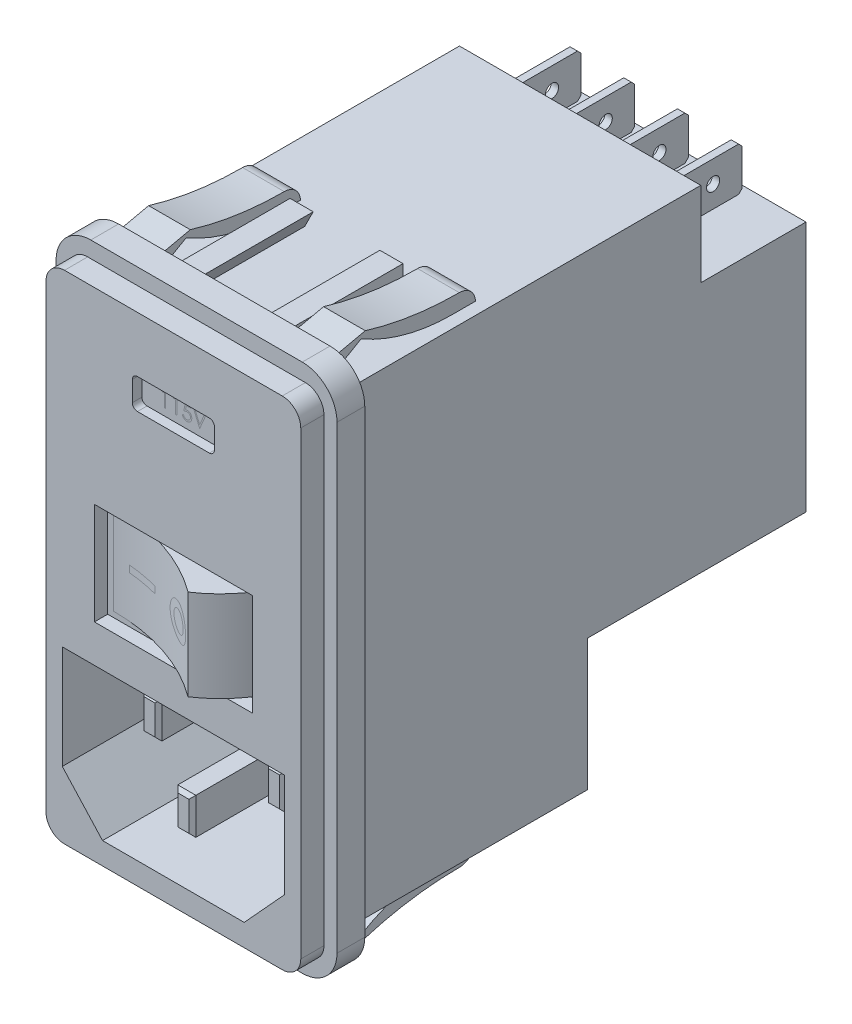
SolidWorks part; units mm, degrees
ref_plane "Front Plane" through (0, 0, 0) normal (0, 0, 1) x (1, 0, 0)
ref_plane "Top Plane" through (0, 0, 0) normal (0, 1, 0) x (1, 0, 0)
ref_plane "Right Plane" through (0, 0, 0) normal (1, 0, 0) x (0, 0, -1)
sketch "Sketch1" plane through (0, 0, 0) normal (0, 0, 1) x (1, 0, 0)
  line L1 (-11.6014, -29.0386) -> (11.6014, -29.0386)
  line L2 (-15.4114, -25.2285) -> (-15.4114, 25.2285)
  line L3 (-11.6014, 29.0386) -> (11.6014, 29.0386)
  line L4 (15.4115, -25.2285) -> (15.4115, 25.2285)
  line L5 (-15.4114, -29.0386) -> (15.4115, 29.0386) construction
  line L6 (-15.4114, 29.0386) -> (15.4115, -29.0386) construction
  arc A0 (-11.6014, -29.0386) -> (-15.4114, -25.2285) centre (-11.6014, -25.2286) cw
  arc A1 (11.6014, -29.0386) -> (15.4115, -25.2285) centre (11.6015, -25.2286) ccw
  arc A2 (11.6014, 29.0386) -> (15.4115, 25.2285) centre (11.6015, 25.2286) cw
  arc A3 (-15.4114, 25.2285) -> (-11.6014, 29.0386) centre (-11.6014, 25.2286) cw
  point P0 (0, 0)
  dimension "D3" = 3.81
  dimension "D1" = 58.0771
  dimension "D2" = 30.8229
extrude "Boss-Extrude1" add sketch "Sketch1" against normal blind 5.588
sketch "Sketch2" plane through (0, 0, 0) normal (0, 0, 1) x (1, 0, 0)
  line L0 (11.6014, 29.0386) -> (-11.6014, 29.0386) construction
  line L1 (-11.9443, -27.2606) -> (11.9443, -27.2606)
  line L2 (-13.9764, -25.2285) -> (-13.9764, 25.2285)
  line L3 (-11.9443, 27.2606) -> (11.9443, 27.2606)
  line L4 (13.9764, -25.2285) -> (13.9764, 25.2285)
  line L5 (-13.9764, -27.2606) -> (13.9764, 27.2606) construction
  line L6 (-13.9764, 27.2606) -> (13.9764, -27.2606) construction
  line L7 (15.4115, -25.2286) -> (15.4115, 25.2285) construction
  line L12 (-11.6014, -29.0386) -> (11.6014, -29.0386)
  line L13 (15.4115, -25.2286) -> (15.4115, 25.2285)
  line L14 (11.6014, 29.0386) -> (-11.6014, 29.0386)
  line L15 (-15.4114, 25.2285) -> (-15.4114, -25.2285)
  line L16 (-11.6014, -29.0386) -> (11.6014, -29.0386)
  line L17 (15.4115, -25.2286) -> (15.4115, 25.2285)
  line L18 (11.6014, 29.0386) -> (-11.6014, 29.0386)
  line L19 (-15.4114, 25.2285) -> (-15.4114, -25.2285)
  arc A0 (-11.9443, -27.2606) -> (-13.9764, -25.2285) centre (-11.9444, -25.2286) cw
  arc A1 (11.9443, -27.2606) -> (13.9764, -25.2285) centre (11.9444, -25.2286) ccw
  arc A2 (11.9443, 27.2606) -> (13.9764, 25.2285) centre (11.9444, 25.2286) cw
  arc A3 (-13.9764, 25.2285) -> (-11.9443, 27.2606) centre (-11.9444, 25.2286) cw
  arc A8 (-15.4114, -25.2285) -> (-11.6014, -29.0386) centre (-11.6014, -25.2286) ccw
  arc A9 (11.6014, -29.0386) -> (15.4115, -25.2286) centre (11.6015, -25.2286) ccw
  arc A10 (15.4115, 25.2285) -> (11.6014, 29.0386) centre (11.6015, 25.2286) ccw
  arc A11 (-11.6014, 29.0386) -> (-15.4114, 25.2285) centre (-11.6014, 25.2286) ccw
  arc A12 (-15.4114, -25.2285) -> (-11.6014, -29.0386) centre (-11.6014, -25.2286) ccw
  arc A13 (11.6014, -29.0386) -> (15.4115, -25.2286) centre (11.6015, -25.2286) ccw
  arc A14 (15.4115, 25.2285) -> (11.6014, 29.0386) centre (11.6015, 25.2286) ccw
  arc A15 (-11.6014, 29.0386) -> (-15.4114, 25.2285) centre (-11.6014, 25.2286) ccw
  point P0 (0, 0)
  dimension "D3" = 2.032
  dimension "D1" = 1.778
  dimension "D2" = 1.4351
  dimension "D4" = 0
extrude "Cut-Extrude1" cut sketch "Sketch2" against normal blind 2.54
sketch "Sketch4" plane through (0, 0, -5.588) normal (0, 0, -1) x (-1, 0, 0)
  line L1 (-13.2398, -25.6096) -> (13.2397, -25.6096)
  line L2 (-13.2398, -25.6096) -> (-13.2398, 25.6096)
  line L3 (-13.2398, 25.6096) -> (13.2397, 25.6096)
  line L4 (13.2397, -25.6096) -> (13.2397, 25.6096)
  line L5 (-13.2398, -25.6096) -> (13.2397, 25.6096) construction
  line L6 (-13.2398, 25.6096) -> (13.2397, -25.6096) construction
  point P0 (0, 0)
  dimension "D1" = 51.2191
  dimension "D2" = 26.4795
extrude "Boss-Extrude2" add sketch "Sketch4" along normal blind 50.5841
sketch "Sketch3" plane through (0, 0, 0) normal (0, 0, 1) x (1, 0, 0)
  line L0 (-12.192, -20.0089) -> (-7.7724, -24.8476)
  line L1 (-12.192, -20.0089) -> (12.192, -20.0089) construction
  line L2 (-12.192, -20.0089) -> (-12.192, -8.6424)
  line L3 (-12.192, -8.6424) -> (12.192, -8.6424)
  line L4 (12.192, -20.0089) -> (12.192, -8.6424)
  line L5 (-12.192, -20.0089) -> (12.192, -8.6424) construction
  line L6 (-12.192, -8.6424) -> (12.192, -20.0089) construction
  line L7 (-7.7724, -24.8476) -> (7.7724, -24.8476)
  line L8 (7.7724, -24.8476) -> (12.192, -20.0089)
  line L9 (-11.6014, -29.0386) -> (11.6014, -29.0386) construction
  point P0 (0, -14.3256)
  point P5 (0, -24.8476)
  dimension "D1" = 24.384
  dimension "D2" = 11.3665
  dimension "D3" = 16.2052
  dimension "D4" = 4.4196
  dimension "D5" = 4.191
extrude "Cut-Extrude2" cut sketch "Sketch3" against normal blind 16.51
sketch "Sketch5" plane through (0, 0, -16.51) normal (0, 0, 1) x (1, 0, 0)
  line L0 (0, -8.6424) -> (0, -24.8476) construction
  line L1 (-7.8232, -12.7191) -> (-5.842, -12.7191)
  line L2 (-7.8232, -12.7191) -> (-7.8232, -16.7196)
  line L3 (-7.8232, -16.7196) -> (-5.842, -16.7196)
  line L4 (-5.842, -12.7191) -> (-5.842, -16.7196)
  line L5 (5.842, -12.7191) -> (7.8232, -12.719)
  line L6 (5.842, -12.7191) -> (5.842, -16.7196)
  line L7 (5.842, -16.7196) -> (7.8232, -16.7195)
  line L8 (7.8232, -12.719) -> (7.8232, -16.7195)
  line L9 (-0.9906, -16.8974) -> (0.9906, -16.8974) construction
  line L10 (-0.9906, -16.8974) -> (-0.9906, -20.8979) construction
  line L11 (-0.9906, -20.8979) -> (0.9906, -20.8979) construction
  line L12 (0.9906, -16.8974) -> (0.9906, -20.8979) construction
  line L13 (12.192, -8.6424) -> (-12.192, -8.6424) construction
  line L14 (-7.7724, -24.8476) -> (7.7724, -24.8476) construction
  line L15 (-7.7724, -24.8476) -> (7.7724, -24.8476) construction
  line L16 (-12.192, -8.6424) -> (-12.192, -20.0089) construction
  dimension "D1" = 1.9812
  dimension "D2" = 4.0005
  dimension "D3" = 8.255
  dimension "D4" = 8.128
  dimension "D5" = 4.3688
extrude "Boss-Extrude3" add sketch "Sketch5" along normal blind 12.3063
sketch "Sketch6" plane through (0, 0, -16.51) normal (0, 0, 1) x (1, 0, 0)
  line L0 (-0.9906, -16.8974) -> (0.9906, -16.8974) construction
  line L1 (0.9906, -16.8974) -> (0.9906, -20.8979) construction
  line L2 (-0.9906, -20.8979) -> (0.9906, -20.8979) construction
  line L3 (-0.9906, -16.8974) -> (-0.9906, -20.8979) construction
  line L4 (-0.9906, -16.8974) -> (0.9906, -16.8974)
  line L5 (0.9906, -16.8974) -> (0.9906, -20.8979)
  line L6 (-0.9906, -20.8979) -> (0.9906, -20.8979)
  line L7 (-0.9906, -16.8974) -> (-0.9906, -20.8979)
extrude "Boss-Extrude4" add sketch "Sketch6" along normal blind 15.4178
sketch "Sketch7" plane through (0, 0, 0) normal (0, 0, 1) x (1, 0, 0)
  line L0 (12.192, -8.6424) -> (-12.192, -8.6424) construction
  line L1 (-8.6678, 6.6611) -> (8.6677, 6.6611)
  line L2 (-8.6678, 6.6611) -> (-8.6677, -4.5149)
  line L3 (-8.6677, -4.5149) -> (8.6677, -4.5149)
  line L4 (8.6677, 6.6611) -> (8.6677, -4.5149)
  line L5 (-8.6678, 6.6611) -> (8.6677, -4.5149) construction
  line L6 (-8.6677, -4.5149) -> (8.6677, 6.6611) construction
  point P0 (0, 1.0731)
  dimension "D1" = 17.3355
  dimension "D2" = 11.176
  dimension "D3" = 4.1275
extrude "Cut-Extrude3" cut sketch "Sketch7" against normal blind 1.4605
ref_plane "Plane1" through (0, 1.0731, 0) normal (0, -1, 0) x (-1, 0, 0)
sketch "Sketch8" plane through (0, 1.0731, 0) normal (0, -1, 0) x (-1, 0, 0)
  line L0 (8.0582, 1.4605) -> (-8.0582, 1.4605)
  line L1 (-8.6677, 1.4605) -> (8.6678, 1.4605) construction
  line L2 (-4.1974, -2.5908) -> (-4.1974, 1.4605) construction
  line L3 (8.0582, 1.4605) -> (8.0582, -2.5908) construction
  line L4 (8.0582, -2.5908) -> (-8.0582, -2.5908) construction
  line L5 (-8.0582, -2.5908) -> (-8.0582, 1.4605) construction
  line L6 (8.6678, 1.4605) -> (8.6678, 0) construction
  arc A0 (-8.0582, 1.4605) -> (-4.1974, -2.5908) centre (2.8401, 7.981) ccw
  arc A1 (-4.1974, -2.5908) -> (8.0582, 1.4605) centre (8.0582, -19.1021) cw
  point P12 (0, -2.5908)
  dimension "D4" = 12.7
  dimension "D1" = 4.0513
  dimension "D2" = 0.6096
  dimension "D3" = 3.8608
extrude "Boss-Extrude5" add sketch "Sketch8" against normal offset from surface 0.6096 and the other way offset from surface (4.9784 mm away) 0.6096 up to face at (0, 6.6611, -0.7302) other way up to face at (0, -4.5149, -0.7302)
sketch "Sketch9" plane through (0, 0, 0) normal (0, 0, 1) x (1, 0, 0)
  line L0 (11.9443, 27.2606) -> (-11.9443, 27.2606) construction
  line L1 (-3.9497, 17.8372) -> (3.9497, 17.8372)
  line L2 (-4.5085, 18.396) -> (-4.5085, 20.6057)
  line L3 (-3.9497, 21.1646) -> (3.9497, 21.1646)
  line L4 (4.5085, 18.396) -> (4.5085, 20.6057)
  line L5 (-4.5085, 17.8372) -> (4.5085, 21.1646) construction
  line L6 (-4.5085, 21.1646) -> (4.5085, 17.8372) construction
  arc A0 (3.9497, 17.8372) -> (4.5085, 18.396) centre (3.9497, 18.3959) ccw
  arc A1 (3.9497, 21.1646) -> (4.5085, 20.6057) centre (3.9497, 20.6058) cw
  arc A2 (-3.9497, 17.8372) -> (-4.5085, 18.396) centre (-3.9497, 18.3959) cw
  arc A3 (-4.5085, 20.6057) -> (-3.9497, 21.1646) centre (-3.9497, 20.6058) cw
  point P0 (0, 19.5008)
  dimension "D4" = 0.5588
  dimension "D1" = 9.017
  dimension "D2" = 3.3274
  dimension "D3" = 6.096
extrude "Cut-Extrude4" cut sketch "Sketch9" against normal blind 1.0541
sketch "Sketch10" plane through (13.2398, 0, 0) normal (1, 0, 0) x (0, 0, -1)
  line L1 (56.1721, 25.6096) -> (44.6278, 25.6096)
  line L2 (56.1721, 25.6096) -> (56.1721, 16.3513)
  line L3 (56.1721, 16.3513) -> (44.6278, 16.3513)
  line L4 (44.6278, 25.6096) -> (44.6278, 16.3513)
  line L5 (56.1721, -25.6096) -> (32.1945, -25.6096)
  line L6 (56.1721, -25.6096) -> (56.1721, -11.2078)
  line L7 (56.1721, -11.2078) -> (32.1945, -11.2078)
  line L8 (32.1945, -25.6096) -> (32.1945, -11.2078)
  dimension "D1" = 23.9776
  dimension "D2" = 14.4018
  dimension "D3" = 9.2583
  dimension "D4" = 11.5443
extrude "Cut-Extrude5" cut sketch "Sketch10" against normal through all
sketch "Sketch11" plane through (0, 0, -44.6278) normal (0, 0, -1) x (-1, 0, 0)
  line L0 (0, 0) -> (0, 25.6096) construction
  line L1 (-9.2456, 23.4633) -> (-8.4328, 23.4633)
  line L2 (-9.2456, 23.4633) -> (-9.2456, 18.6754)
  line L3 (-9.2456, 18.6754) -> (-8.4328, 18.6754)
  line L4 (-8.4328, 23.4633) -> (-8.4328, 18.6754)
  line L5 (-9.2456, 23.4633) -> (-8.4328, 18.6754) construction
  line L6 (-9.2456, 18.6754) -> (-8.4328, 23.4633) construction
  line L7 (-3.3528, 23.4633) -> (-2.54, 23.4633)
  line L8 (-3.3528, 23.4633) -> (-3.3528, 18.6754)
  line L9 (-3.3528, 18.6754) -> (-2.54, 18.6754)
  line L10 (-2.54, 23.4633) -> (-2.54, 18.6754)
  line L11 (-3.3528, 23.4633) -> (-2.54, 18.6754) construction
  line L12 (-3.3528, 18.6754) -> (-2.54, 23.4633) construction
  line L13 (2.54, 23.4633) -> (3.3528, 23.4633)
  line L14 (2.54, 23.4633) -> (2.54, 18.6754)
  line L15 (2.54, 18.6754) -> (3.3528, 18.6754)
  line L16 (3.3528, 23.4633) -> (3.3528, 18.6754)
  line L17 (2.54, 23.4633) -> (3.3528, 18.6754) construction
  line L18 (2.54, 18.6754) -> (3.3528, 23.4633) construction
  line L19 (8.4328, 23.4633) -> (9.2456, 23.4633)
  line L20 (8.4328, 23.4633) -> (8.4328, 18.6754)
  line L21 (8.4328, 18.6754) -> (9.2456, 18.6754)
  line L22 (9.2456, 23.4633) -> (9.2456, 18.6754)
  line L23 (8.4328, 23.4633) -> (9.2456, 18.6754) construction
  line L24 (8.4328, 18.6754) -> (9.2456, 23.4633) construction
  line L25 (13.2397, 25.6096) -> (-13.2398, 25.6096) construction
  point P0 (-8.8392, 21.0693)
  point P5 (-2.9464, 21.0693)
  point P10 (2.9464, 21.0693)
  point P15 (8.8392, 21.0693)
  dimension "D1" = 4.7879
  dimension "D2" = 0.8128
  dimension "D3" = 5.08
  dimension "D4" = 5.08
  dimension "D5" = 2.1463
extrude "Boss-Extrude6" add sketch "Sketch11" along normal blind 8.5217
sketch "Sketch12" plane through (9.2456, 0, 0) normal (1, 0, 0) x (0, 0, -1)
  line L1 (53.1495, 23.4633) -> (53.1495, 18.6754) construction
  line L2 (53.1495, 21.0693) -> (49.9745, 21.0693) construction
  circle A0 centre (49.9745, 21.0693) radius 0.7239
  dimension "D1" = 1.4478
  dimension "D2" = 3.175
extrude "Cut-Extrude6" cut sketch "Sketch12" against normal through all
sketch "Sketch13" plane through (0, 0, -32.1945) normal (0, 0, -1) x (-1, 0, 0)
  line L0 (-5.6959, -11.2078) -> (5.696, -11.2078)
  line L1 (5.696, -11.2078) -> (6.9469, -14.1034)
  line L2 (6.9469, -14.1034) -> (-6.9469, -14.1034)
  line L3 (-6.9469, -14.1034) -> (-5.6959, -11.2078)
  line L4 (0, 0) -> (0, -25.6096) construction
  line L5 (-13.2398, -25.6096) -> (13.2397, -25.6096) construction
  line L6 (-13.2398, -11.2078) -> (13.2397, -11.2078) construction
  point P9 (0, -11.2078)
  point P10 (0, -14.1034)
  dimension "D1" = 2.8956
  dimension "D2" = 13.8938
  dimension "D3" = 11.3919
extrude "Boss-Extrude7" add sketch "Sketch13" along normal offset from surface (8.4201 mm away) 15.5575 up to face at (0, 2.5718, -56.1721)
sketch "Sketch14" plane through (0, 0, -32.1945) normal (0, 0, -1) x (-1, 0, 0)
  line L0 (0, 0) -> (0, -25.6096) construction
  line L1 (-9.4932, -18.3706) -> (-6.3691, -18.3706)
  line L2 (-10.1537, -19.031) -> (-10.1537, -22.7901)
  line L3 (-9.4932, -23.4506) -> (-6.3691, -23.4506)
  line L4 (-5.7087, -19.031) -> (-5.7087, -22.7901)
  line L9 (-13.2398, -25.6096) -> (13.2397, -25.6096) construction
  line L10 (-13.2398, -11.2078) -> (-13.2398, -25.6096) construction
  line L11 (13.2397, -25.6096) -> (-13.2398, -25.6096) construction
  line L12 (-9.3917, -19.1326) -> (-6.4707, -19.1326)
  line L13 (-6.4707, -19.1326) -> (-6.4707, -22.6886)
  line L14 (-9.3917, -22.6886) -> (-6.4707, -22.6886)
  line L15 (-9.3917, -19.1326) -> (-9.3917, -22.6886)
  line L16 (9.3916, -19.1326) -> (9.3916, -22.6886)
  line L17 (9.3916, -22.6886) -> (6.4706, -22.6886)
  line L18 (6.4707, -19.1326) -> (6.4706, -22.6886)
  line L19 (9.3916, -19.1326) -> (6.4707, -19.1326)
  line L20 (5.7087, -19.031) -> (5.7086, -22.7901)
  line L21 (9.4932, -23.4506) -> (6.3691, -23.4506)
  line L22 (10.1536, -19.031) -> (10.1536, -22.7901)
  line L23 (9.4932, -18.3706) -> (6.3691, -18.3706)
  arc A0 (-10.1537, -22.7901) -> (-9.4932, -23.4506) centre (-9.4933, -22.7902) ccw
  arc A1 (-6.3691, -23.4506) -> (-5.7087, -22.7901) centre (-6.3691, -22.7902) ccw
  arc A2 (-6.3691, -18.3706) -> (-5.7087, -19.031) centre (-6.3691, -19.031) cw
  arc A3 (-9.4932, -18.3706) -> (-10.1537, -19.031) centre (-9.4933, -19.031) ccw
  arc A4 (-6.4707, -19.1326) -> (-6.4707, -19.1326) centre (-6.4707, -19.1326) cw
  arc A5 (-6.4707, -22.6886) -> (-6.4707, -22.6886) centre (-6.4707, -22.6886) ccw
  arc A6 (-9.3917, -22.6886) -> (-9.3917, -22.6886) centre (-9.3917, -22.6886) ccw
  arc A7 (-9.3917, -19.1326) -> (-9.3917, -19.1326) centre (-9.3917, -19.1326) ccw
  arc A8 (9.4932, -18.3706) -> (10.1536, -19.031) centre (9.4932, -19.031) cw
  arc A9 (6.3691, -18.3706) -> (5.7087, -19.031) centre (6.369, -19.031) ccw
  arc A10 (6.3691, -23.4506) -> (5.7086, -22.7901) centre (6.369, -22.7902) cw
  arc A11 (10.1536, -22.7901) -> (9.4932, -23.4506) centre (9.4932, -22.7902) cw
  point P5 (10.1536, -18.3706)
  point P19 (-10.1537, -23.4506)
  point P22 (-5.7087, -23.4506)
  point P27 (-10.1537, -18.3706)
  point P40 (5.7086, -23.4506)
  point P54 (10.1536, -23.4506)
  dimension "D5" = 0.6604
  dimension "D1" = 4.445
  dimension "D2" = 5.08
  dimension "D3" = 3.0861
  dimension "D4" = 2.159
  dimension "D6" = 0.762
extrude "Boss-Extrude8" add sketch "Sketch14" along normal blind 1.524
sketch "Sketch15" plane through (0, 0, -32.1945) normal (0, 0, -1) x (-1, 0, 0)
  line L0 (13.2397, -25.6096) -> (-13.2398, -25.6096) construction
  line L1 (-3.2639, -14.1034) -> (3.2639, -14.1034)
  line L2 (-3.2639, -14.1034) -> (-3.2639, -25.6096)
  line L3 (-3.2639, -25.6096) -> (3.2639, -25.6096)
  line L4 (3.2639, -14.1034) -> (3.2639, -25.6096)
  line L5 (-3.2639, -14.1034) -> (3.2639, -25.6096) construction
  line L6 (-3.2639, -25.6096) -> (3.2639, -14.1034) construction
  line L7 (-6.9469, -14.1034) -> (6.9469, -14.1034) construction
  point P0 (0, -19.8565)
  dimension "D1" = 6.5278
extrude "Cut-Extrude7" cut sketch "Sketch15" against normal blind 5.0165
sketch "Sketch16" plane through (0, 0, -27.178) normal (0, 0, -1) x (-1, 0, 0)
  line L0 (-3.2639, -25.6096) -> (3.2639, -25.6096) construction
  line L1 (-0.381, -15.7544) -> (0.381, -15.7544)
  line L2 (-0.381, -15.7544) -> (-0.381, -20.5296)
  line L3 (-0.381, -20.5296) -> (0.381, -20.5296)
  line L4 (0.381, -15.7544) -> (0.381, -20.5296)
  line L5 (-0.381, -15.7544) -> (0.381, -20.5296) construction
  line L6 (-0.381, -20.5296) -> (0.381, -15.7544) construction
  point P0 (0, -18.142)
  dimension "D1" = 4.7752
  dimension "D2" = 0.762
  dimension "D3" = 5.08
extrude "Boss-Extrude9" add sketch "Sketch16" along normal blind 8.5979
sketch "Sketch17" plane through (0.381, 0, 0) normal (1, 0, 0) x (0, 0, -1)
  line L0 (35.7759, -15.7544) -> (35.7759, -20.5296) construction
  line L1 (31.3944, -18.8405) -> (32.5374, -18.8405)
  line L2 (31.3944, -18.8405) -> (31.3944, -17.4435) construction
  line L3 (31.3944, -17.4435) -> (32.5374, -17.4435)
  line L4 (32.5374, -18.8405) -> (32.5374, -17.4435) construction
  line L5 (31.3944, -18.8405) -> (32.5374, -17.4435) construction
  line L6 (31.3944, -17.4435) -> (32.5374, -18.8405) construction
  arc A0 (31.3944, -17.4435) -> (31.3944, -18.8405) centre (31.3944, -18.142) ccw
  arc A1 (32.5374, -17.4435) -> (32.5374, -18.8405) centre (32.5374, -18.142) cw
  point P0 (31.9659, -18.142)
  point P8 (35.7759, -18.142)
  point P10 (30.6959, -18.142)
  point P11 (33.2359, -18.142)
  dimension "D1" = 2.54
  dimension "D2" = 2.54
  dimension "D3" = 1.397
extrude "Cut-Extrude8" cut sketch "Sketch17" against normal up to surface (0.762 mm away) up to face at (-0.381, -18.142, -31.477)
chamfer "Chamfer1" distance 0.381 angle 45 22 edges at (6.8326, -12.719, -4.2037) (7.8232, -14.7193, -4.2037) (6.8326, -16.7195, -4.2037) (5.842, -14.7193, -4.2037) (0, -16.8974, -1.0922) (0.9906, -18.8976, -1.0922) (0, -20.8979, -1.0922) (-0.9906, -18.8976, -1.0922) (-6.8326, -12.7191, -4.2037) (-5.842, -14.7193, -4.2037) (-6.8326, -16.7196, -4.2037) (-7.8232, -14.7193, -4.2037) (-2.9464, 18.6754, -53.1495) (-8.8392, 18.6754, -53.1495) (-8.8392, 23.4633, -53.1495) (-2.9464, 23.4633, -53.1495) (2.9464, 18.6754, -53.1495) (2.9464, 23.4633, -53.1495) (8.8392, 18.6754, -53.1495) (8.8392, 23.4633, -53.1495) (0, -20.5296, -35.7759) (0, -15.7544, -35.7759)
sketch "Sketch18" plane through (0, 0, -5.588) normal (0, 0, -1) x (-1, 0, 0)
  line L0 (0, 29.0386) -> (0, -29.0386) construction
  line L1 (-11.6014, 29.0386) -> (11.6014, 29.0386) construction
  line L2 (11.6014, -29.0386) -> (-11.6014, -29.0386) construction
  line L3 (-15.4115, 0) -> (15.4114, 0) construction
  line L4 (-15.4115, -25.2286) -> (-15.4115, 25.2285) construction
  line L5 (15.4114, 25.2285) -> (15.4114, -25.2285) construction
  line L6 (-6.1976, 25.6096) -> (-4.5847, 25.6096)
  line L7 (13.2397, 25.6096) -> (-13.2398, 25.6096) construction
  line L8 (-6.1976, 25.6096) -> (-6.1976, 27.4638)
  line L9 (-6.1976, 27.4638) -> (-3.6576, 27.4638)
  line L10 (-3.6576, 27.4638) -> (-4.5847, 25.6096)
  line L11 (3.6576, 27.4638) -> (4.5847, 25.6096)
  line L12 (6.1976, 27.4638) -> (3.6576, 27.4638)
  line L13 (6.1976, 25.6096) -> (6.1976, 27.4638)
  line L14 (6.1976, 25.6096) -> (4.5847, 25.6096)
  line L15 (6.1976, -25.6096) -> (4.5847, -25.6096)
  line L16 (6.1976, -25.6096) -> (6.1976, -27.4638)
  line L17 (6.1976, -27.4638) -> (3.6576, -27.4638)
  line L18 (3.6576, -27.4638) -> (4.5847, -25.6096)
  line L19 (-3.6576, -27.4638) -> (-4.5847, -25.6096)
  line L20 (-6.1976, -27.4638) -> (-3.6576, -27.4638)
  line L21 (-6.1976, -25.6096) -> (-6.1976, -27.4638)
  line L22 (-6.1976, -25.6096) -> (-4.5847, -25.6096)
  dimension "D1" = 2.54
  dimension "D2" = 1.8542
  dimension "D3" = 1.6129
  dimension "D4" = 3.6576
extrude "Boss-Extrude10" add sketch "Sketch18" along normal blind 13.4112
ref_plane "Plane2" through (7.3152, 0, 0) normal (1, 0, 0) x (0, 0, -1)
sketch "Sketch19" plane through (7.3152, 0, 0) normal (1, 0, 0) x (0, 0, -1)
  line L0 (21.2598, 25.6096) -> (18.7198, 25.6096)
  line L1 (44.6278, 25.6096) -> (5.588, 25.6096) construction
  line L2 (8.7122, 28.302) -> (6.5786, 27.0701)
  line L3 (6.5786, 27.0701) -> (6.0198, 28.1495)
  line L4 (6.0198, 28.1495) -> (9.1694, 28.8481)
  line L5 (6.0198, 28.1495) -> (21.2598, 28.1495) construction
  line L6 (21.2598, 28.1495) -> (21.2598, 25.6096) construction
  line L7 (18.9992, 25.6096) -> (5.588, 25.6096) construction
  line L9 (21.2598, 28.1495) -> (21.2598, 27.3114) construction
  line L10 (21.2598, 27.3114) -> (19.4818, 27.3114) construction
  line L11 (5.588, 25.2285) -> (5.588, 29.0386) construction
  line L12 (0, 0) -> (56.1721, 0) construction
  line L13 (0, -25.2286) -> (0, 25.2285) construction
  line L14 (56.1721, 16.3513) -> (56.1721, -11.2078) construction
  line L15 (21.2598, -27.3114) -> (19.4818, -27.3114) construction
  line L16 (21.2598, -28.1496) -> (21.2598, -27.3114) construction
  line L17 (21.2598, -28.1496) -> (21.2598, -25.6096) construction
  line L18 (6.0198, -28.1496) -> (21.2598, -28.1496) construction
  line L19 (6.0198, -28.1496) -> (9.1694, -28.8481)
  line L20 (6.5786, -27.0701) -> (6.0198, -28.1496)
  line L21 (8.7122, -28.302) -> (6.5786, -27.0701)
  line L22 (21.2598, -25.6096) -> (18.7198, -25.6096)
  arc A0 (18.7198, 25.6096) -> (8.7122, 28.302) centre (18.7198, 45.5548) cw
  arc A1 (9.1694, 28.8481) -> (19.4818, 27.3114) centre (19.4818, 62.6816) ccw
  arc A2 (21.2598, 25.6096) -> (19.4818, 27.3114) centre (19.4818, 25.5316) ccw
  arc A3 (21.2598, -25.6096) -> (19.4818, -27.3114) centre (19.4818, -25.5316) cw
  arc A4 (9.1694, -28.8481) -> (19.4818, -27.3114) centre (19.4818, -62.6816) cw
  arc A5 (18.7198, -25.6096) -> (8.7122, -28.302) centre (18.7198, -45.5548) ccw
  dimension "D1" = 15.24
  dimension "D2" = 2.54
  dimension "D3" = 0.4318
  dimension "D4" = 1.7018
  dimension "D5" = 12.0904
  dimension "D6" = 1.778
  dimension "D7" = 2.54
  dimension "D8" = 3.2385
  dimension "D9" = 1.4605
  dimension "D10" = 2.6924
  dimension "D11" = 2.6924
  dimension "D12" = 2.1336
extrude "Boss-Extrude11" add sketch "Sketch19" along normal blind 4.572
mirror "Mirror1" about plane through (0, 0, 0) normal (1, 0, 0) of "Boss-Extrude11"
sketch "Sketch20" plane through (0, 0, -1.0541) normal (0, 0, 1) x (1, 0, 0)
  line L0 (-3.175, 18.5991) -> (3.175, 18.5991) construction
  line L1 (-3.9497, 17.8372) -> (3.9497, 17.8372) construction
  line L2 (-3.9497, 17.8372) -> (3.9497, 17.8372) construction
  text T0 "115V" font "Century Gothic" height 1.5875
  point P2 (0, 18.5991)
  point P5 (0, 17.8372)
  dimension "D1" = 6.35
  dimension "D2" = 0.762
split line "Split Line1"
ref_plane "Plane3" through (0, 0, 2.5908) normal (0, 0, 1) x (1, 0, 0)
sketch "Sketch21" plane through (0, 0, 2.5908) normal (0, 0, 1) x (1, 0, 0)
  line L0 (-2.7877, 1.0731) -> (-0.2985, 1.0731) construction
  line L1 (-6.2167, 1.4414) -> (-2.7877, 1.4414)
  line L2 (-6.2167, 1.4414) -> (-6.2167, 0.7048)
  line L3 (-6.2167, 0.7048) -> (-2.7877, 0.7048)
  line L4 (-2.7877, 1.4414) -> (-2.7877, 0.7048)
  line L5 (-6.2167, 1.4414) -> (-2.7877, 0.7048) construction
  line L6 (-6.2167, 0.7048) -> (-2.7877, 1.4414) construction
  line L7 (4.1974, 6.0515) -> (4.1974, -3.9053) construction
  line L8 (-8.0582, 6.0516) -> (-8.0582, -3.9053) construction
  circle A0 centre (1.5049, 1.0731) radius 1.8034
  circle A1 centre (1.5049, 1.0731) radius 1.0668
  point P3 (-4.5022, 1.0731)
  point P12 (4.1974, 1.0731)
  dimension "D1" = 0.7366
  dimension "D2" = 3.6068
  dimension "D3" = 0.7366
  dimension "D4" = 3.429
  dimension "D5" = 2.4892
  dimension "D6" = 1.8415
split line "Split Line2"
